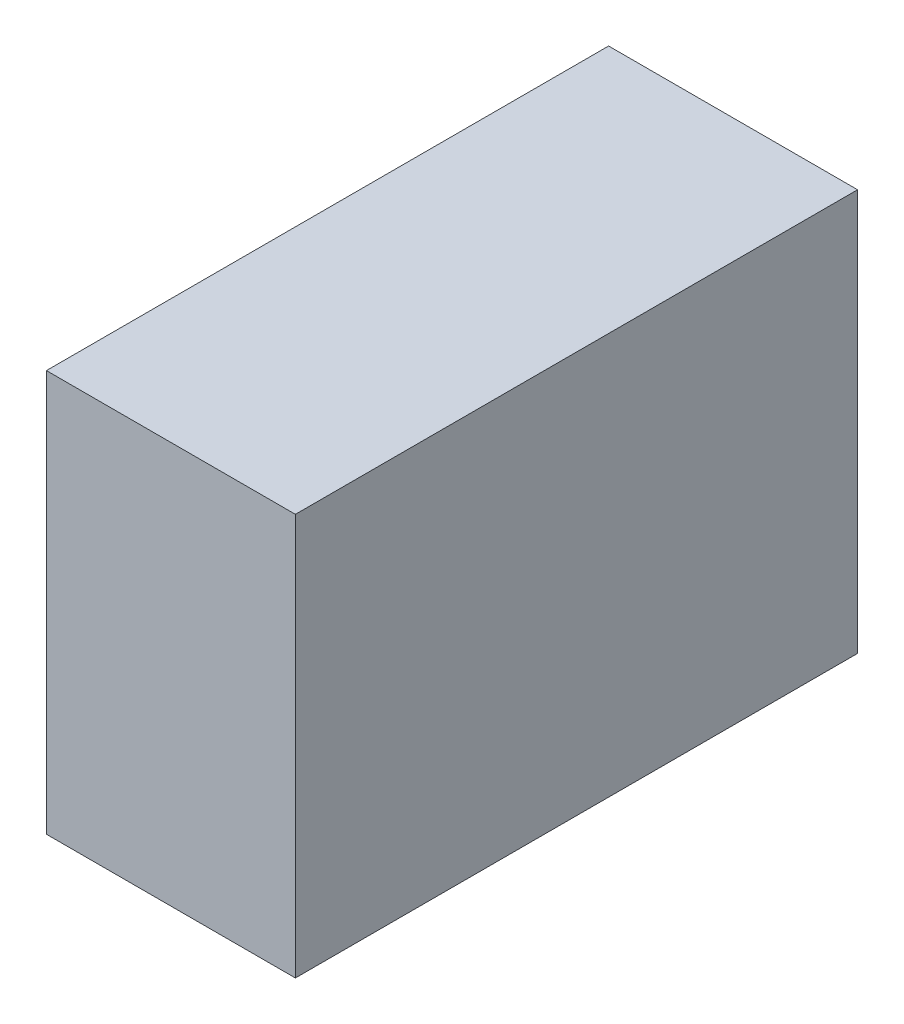
SolidWorks part; units mm, degrees
ref_plane "Front Plane" through (0, 0, 0) normal (0, 0, 1) x (1, 0, 0)
ref_plane "Top Plane" through (0, 0, 0) normal (0, 1, 0) x (1, 0, 0)
ref_plane "Right Plane" through (0, 0, 0) normal (1, 0, 0) x (0, 0, -1)
sketch "Sketch1" plane through (0, 0, 0) normal (0, 1, 0) x (1, 0, 0)
  line L1 (-19.685, -44.45) -> (19.685, -44.45)
  line L2 (-19.685, -44.45) -> (-19.685, 44.45)
  line L3 (-19.685, 44.45) -> (19.685, 44.45)
  line L4 (19.685, -44.45) -> (19.685, 44.45)
  line L5 (-19.685, -44.45) -> (19.685, 44.45) construction
  line L6 (-19.685, 44.45) -> (19.685, -44.45) construction
  point P0 (0, 0)
  dimension "D1" = 88.9
  dimension "D2" = 39.37
extrude "Boss-Extrude1" add sketch "Sketch1" along normal mid plane 63.5
